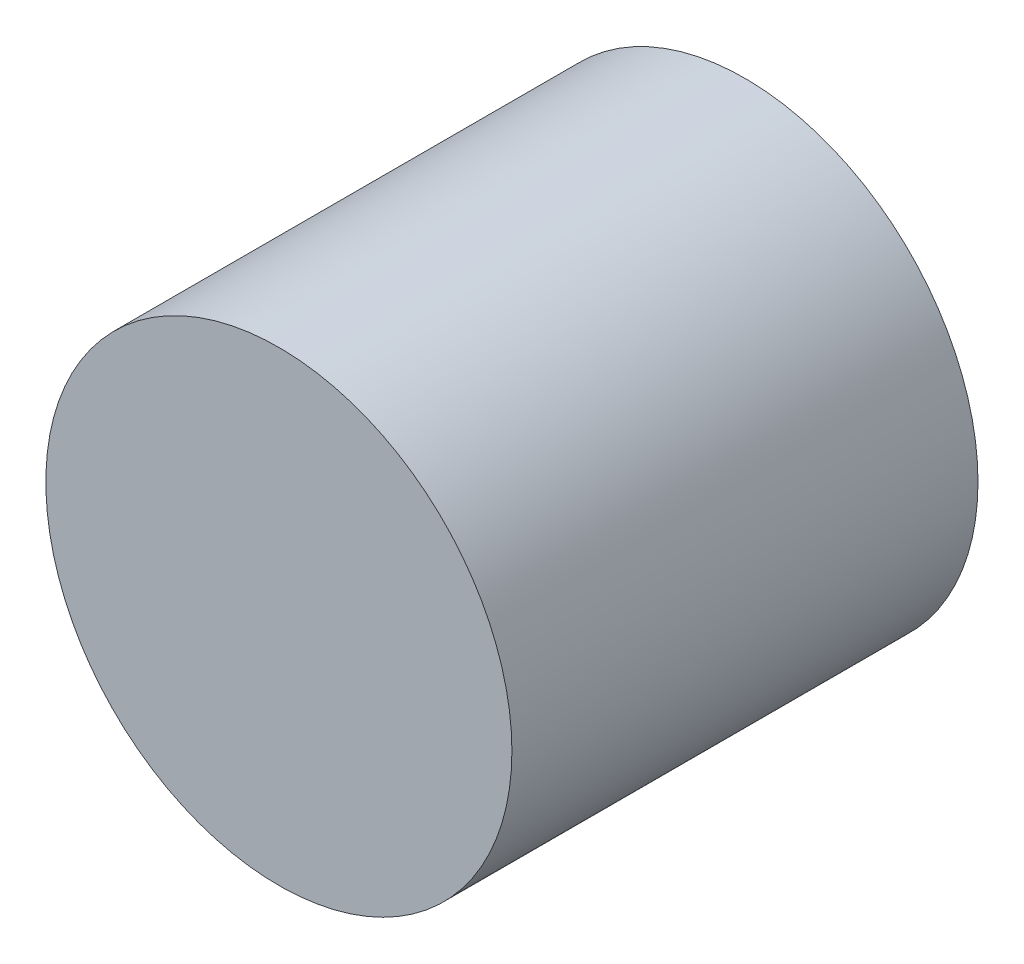
SolidWorks part; units mm, degrees
ref_plane "Front Plane" through (0, 0, 0) normal (0, 0, 1) x (1, 0, 0)
ref_plane "Top Plane" through (0, 0, 0) normal (0, 1, 0) x (1, 0, 0)
ref_plane "Right Plane" through (0, 0, 0) normal (1, 0, 0) x (0, 0, -1)
sketch "Sketch1" plane through (0, 0, 0) normal (0, 0, 1) x (1, 0, 0)
  line L0 (0, 0) -> (0, 640) construction
  circle A0 centre (0, 425.0786) radius 55
  dimension "D2" = 110
  dimension "D1" = 640
extrude "Boss-Extrude1" add sketch "Sketch1" along normal blind 110
